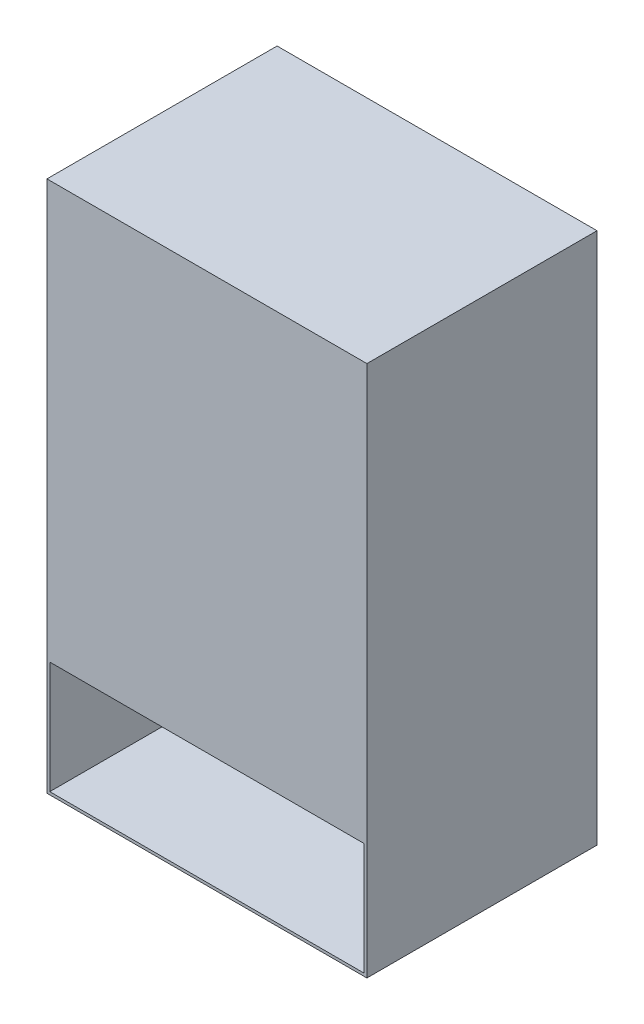
SolidWorks part; units mm, degrees
ref_plane "Plan de face" through (0, 0, 0) normal (0, 0, 1) x (1, 0, 0)
ref_plane "Plan de dessus" through (0, 0, 0) normal (0, 1, 0) x (1, 0, 0)
ref_plane "Plan de droite" through (0, 0, 0) normal (1, 0, 0) x (0, 0, -1)
sketch "Esquisse1" plane through (0, 0, 0) normal (0, 0, 1) x (1, 0, 0)
  line L1 (-180.975, 300.99) -> (180.975, 300.99)
  line L2 (-180.975, 300.99) -> (-180.975, -300.99)
  line L3 (-180.975, -300.99) -> (180.975, -300.99)
  line L4 (180.975, 300.99) -> (180.975, -300.99)
  point P4 (0, 300.99)
  point P6 (180.975, 0)
  dimension "D1" = 361.95
  dimension "D2" = 601.98
extrude "Boss.-Extru.1" add sketch "Esquisse1" along normal mid plane 260.35
sketch "Esquisse3" plane through (0, 0, 130.175) normal (0, 0, 1) x (1, 0, 0)
  line L0 (-180.975, 300.99) -> (-180.975, -300.99) construction
  line L1 (-177.8, -170.815) -> (177.8, -170.815)
  line L2 (-177.8, -170.815) -> (-177.8, -297.815)
  line L3 (-177.8, -297.815) -> (177.8, -297.815)
  line L4 (177.8, -170.815) -> (177.8, -297.815)
  line L5 (180.975, -300.99) -> (180.975, 300.99) construction
  line L6 (-180.975, -300.99) -> (180.975, -300.99) construction
  dimension "D1" = 3.175
  dimension "D2" = 3.175
  dimension "D3" = 3.175
  dimension "D4" = 127
extrude "Enlèv. mat.-Extru.2" cut sketch "Esquisse3" against normal blind 3.175
sketch "Esquisse4" plane through (0, 0, 0) normal (0, 0, 1) x (1, 0, 0)
  line L0 (-177.8, -170.815) -> (-177.8, -297.815) construction
  line L1 (-177.8, 297.815) -> (177.8, 297.815)
  line L2 (-177.8, 297.815) -> (-177.8, -297.815)
  line L3 (-177.8, -297.815) -> (177.8, -297.815)
  line L4 (177.8, 297.815) -> (177.8, -297.815)
  line L5 (177.8, -297.815) -> (177.8, -170.815) construction
  line L6 (-177.8, -297.815) -> (177.8, -297.815) construction
  line L8 (180.975, 300.99) -> (-180.975, 300.99) construction
  dimension "D1" = 3.175
extrude "Enlèv. mat.-Extru.3" cut sketch "Esquisse4" against normal mid plane 254
sketch "Esquisse5" plane through (0, 0, -130.175) normal (0, 0, -1) x (-1, 0, 0)
  line L0 (-180.975, -300.99) -> (-180.975, 300.99) construction
  line L1 (-177.8, 297.815) -> (177.8, 297.815)
  line L2 (-177.8, 297.815) -> (-177.8, 170.815)
  line L3 (-177.8, 170.815) -> (177.8, 170.815)
  line L4 (177.8, 297.815) -> (177.8, 170.815)
  line L5 (180.975, 300.99) -> (180.975, -300.99) construction
  line L6 (-180.975, 300.99) -> (180.975, 300.99) construction
  dimension "D1" = 3.175
  dimension "D2" = 3.175
  dimension "D3" = 3.175
  dimension "D4" = 127
extrude "Enlèv. mat.-Extru.4" cut sketch "Esquisse5" against normal blind 3.175
